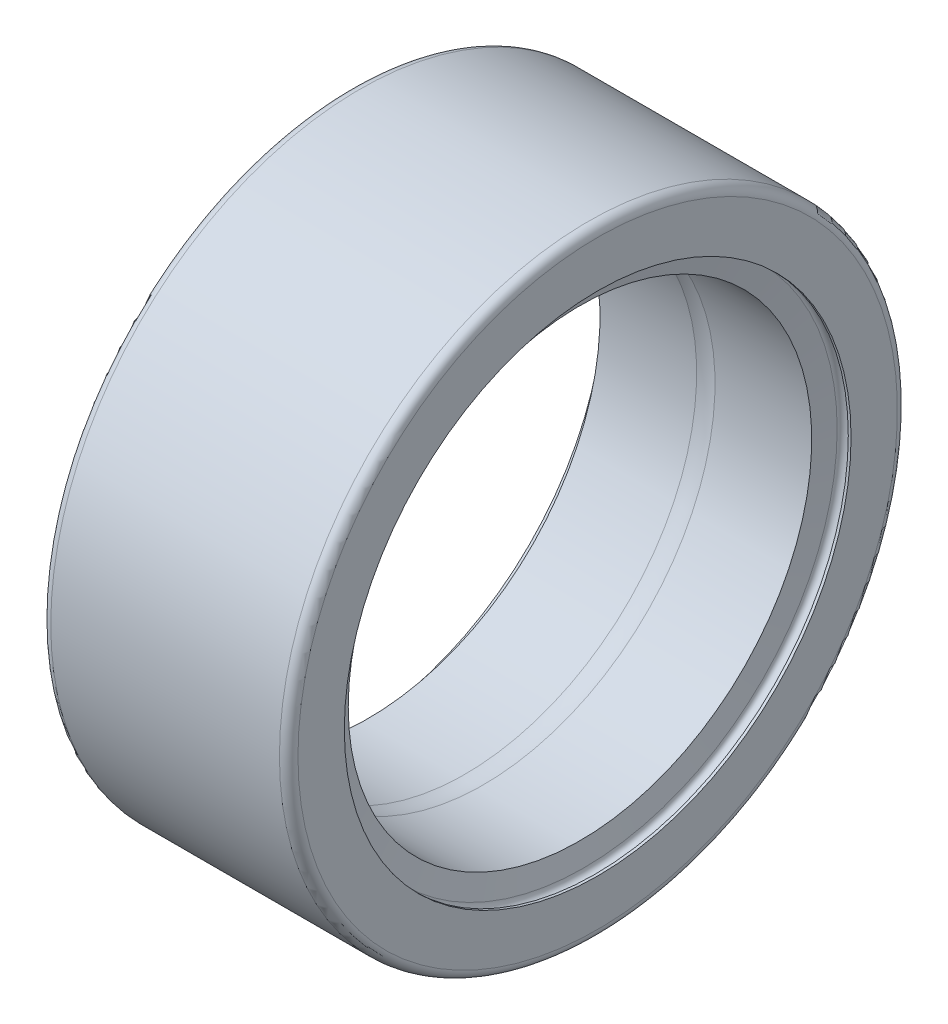
SolidWorks part; units mm, degrees
ref_plane "Front Plane" through (0, 0, 0) normal (0, 0, 1) x (1, 0, 0)
ref_plane "Top Plane" through (0, 0, 0) normal (0, 1, 0) x (1, 0, 0)
ref_plane "Right Plane" through (0, 0, 0) normal (1, 0, 0) x (0, 0, -1)
ref_plane "Plane1" through (0, 0, 0) normal (0, 0, 1) x (1, 0, 0)
sketch "Sketch1" plane through (0, 0, 0) normal (0, 0, 1) x (1, 0, 0)
  line L0 (0, 4.1) -> (0.045, 4.1)
  line L1 (0.225, 4.1) -> (0.2867, 3.75)
  line L2 (0.2867, 3.75) -> (1.8516, 3.75)
  line L3 (2.1484, 3.75) -> (3.7133, 3.75)
  line L4 (3.7133, 3.75) -> (3.775, 4.1)
  line L5 (3.955, 4.1) -> (4, 4.1)
  line L6 (4, 4.1) -> (4, 4.85)
  line L7 (3.85, 5) -> (0.15, 5)
  line L8 (0, 4.85) -> (0, 4.1)
  line L9 (50, 0) -> (-50, 0) construction
  arc A0 (0.045, 4.1) -> (0.225, 4.1) centre (0.135, 4.1) cw
  arc A1 (1.8516, 3.75) -> (2.1484, 3.75) centre (2, 2.97) cw
  arc A2 (3.775, 4.1) -> (3.955, 4.1) centre (3.865, 4.1) cw
  arc A3 (4, 4.85) -> (3.85, 5) centre (3.85, 4.85) ccw
  arc A4 (0.15, 5) -> (0, 4.85) centre (0.15, 4.85) ccw
revolve "Revolve1" add sketch "Sketch1" angle 360 about L9
